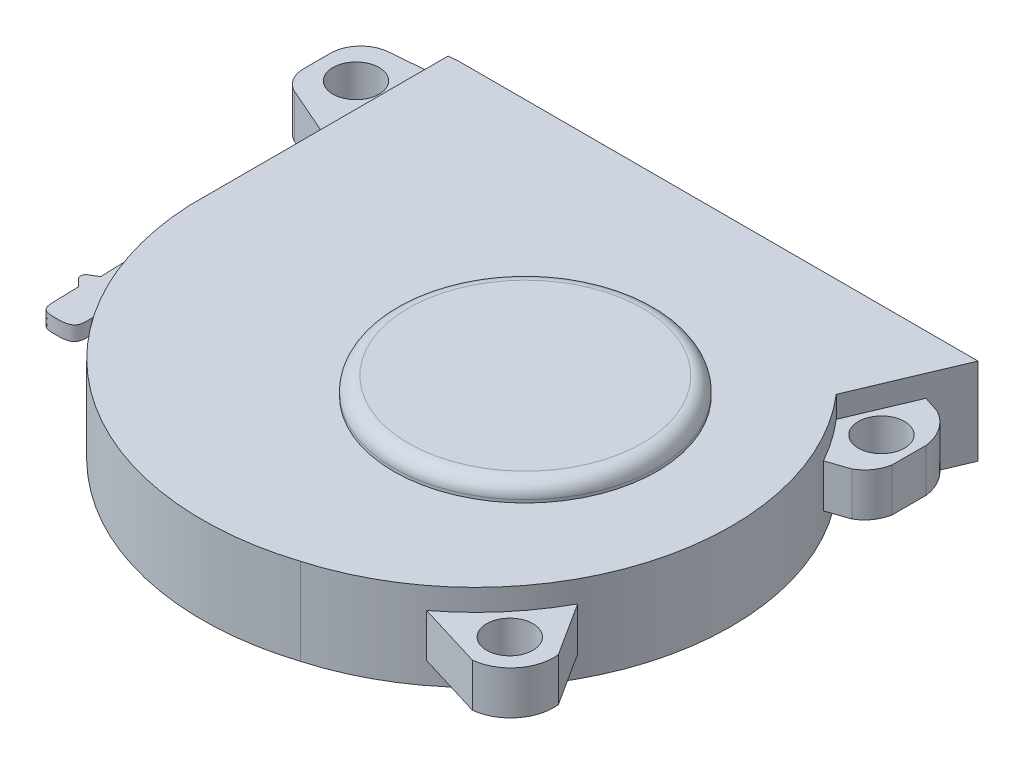
SolidWorks part; units mm, degrees
ref_plane "Front" through (0, 0, 0) normal (0, 0, 1) x (1, 0, 0)
ref_plane "Top" through (0, 0, 0) normal (0, 1, 0) x (1, 0, 0)
ref_plane "Right" through (0, 0, 0) normal (1, 0, 0) x (0, 0, -1)
sketch "Sketch1" plane through (0, 0, 0) normal (0, 1, 0) x (1, 0, 0)
  line L0 (-18.6292, 17.0403) -> (20.0618, 17.0403)
  line L1 (17.6528, 17.8425) -> (14.4091, 10.1398)
  line L2 (16.249, 14.5088) -> (17.4134, 14.1194)
  line L3 (16.45, 7.2111) -> (17.9281, 7.7132)
  line L4 (19.0692, 11.7013) -> (19.0692, 8.3745)
  line L5 (16.5199, -9.8679) -> (19.6981, -14.8328)
  line L6 (11.6896, -15.4846) -> (18.2309, -17.4822)
  line L7 (-18.6292, 17.0403) -> (-27.3062, 16.322)
  line L8 (-25.0308, 14.4047) -> (-25.0308, 12.7056)
  line L9 (-19.2931, 9.001) -> (-28.2152, 12.8944)
  line L10 (-19.2931, -0.9359) -> (-19.2931, 20.8935)
  line L11 (-22.0907, 5.8392) -> (-19.2931, 5.8392)
  line L12 (-23.3574, 4.7836) -> (-23.0966, -3.2535)
  line L13 (-23.0966, -3.2535) -> (-23.6215, -3.5769)
  line L14 (-23.672, -4.2219) -> (-23.0966, -4.7998)
  line L15 (-23.1924, -6.9309) -> (-23.3094, -2.3969)
  line L16 (-20.9157, -6.081) -> (-21.4467, 6.5849)
  line L17 (-20.5996, -3.5931) -> (-21.2439, -3.2731)
  line L18 (-20.5996, -4.1555) -> (-21.1733, -4.78)
  circle A0 centre (-22.4948, 13.8104) radius 1.5
  arc A1 (5.8687, -18.4026) -> (14.4091, 10.1398) centre (0.983, -1.3918) ccw
  arc A2 (5.8687, -18.4026) -> (-19.2931, -0.9359) centre (0, 0) cw
  arc A3 (17.4134, 14.1194) -> (19.0692, 11.7013) centre (15.8644, 11.2827) cw
  arc A4 (17.9281, 7.7132) -> (19.0665, 9.3395) centre (16.7476, 9.7511) ccw
  circle A5 centre (16.8946, 10.7771) radius 1.5
  arc A6 (16.249, -16.8769) -> (18.8914, -13.5727) centre (15.9284, -13.9118) ccw
  circle A7 centre (16.154, -14.1957) radius 1.5
  arc A8 (-25.0308, 14.4047) -> (-23.1116, 16.6692) centre (-22.921, 14.5621) cw
  arc A9 (-25.0308, 12.7056) -> (-23.8371, 10.9839) centre (-23.1924, 12.7056) ccw
  arc A10 (-22.0907, 5.8392) -> (-23.3574, 4.7836) centre (-22.172, 4.649) ccw
  arc A11 (-20.5996, -3.5931) -> (-20.5996, -4.1555) centre (-20.8323, -3.8743) cw
  spline S0 degree 3 poles (-23.2029, -6.5236) (-23.1904, -6.7014) (-23.1459, -7.158) (-22.6046, -7.2916) (-22.1311, -7.3011) (-21.6116, -7.3012) (-20.8501, -7.06) (-20.9152, -6.3528) (-20.9157, -6.081) knots 0 0 0 0 0.172348 0.293809 0.415161 0.571057 0.73062 1 1 1 1
  spline S1 degree 3 poles (-21.2488, 1.8965) (-21.2551, 2.2821) (-21.2272, 3.1094) (-20.2629, 3.6348) (-19.6377, 3.6409) (-19.2931, 3.5168) knots 0 0 0 0 0.425412 0.645509 1 1 1 1
sketch "Sketch2" plane through (0, 0, 0) normal (0, 1, 0) x (1, 0, 0)
  line L0 (16.45, 7.2111) -> (17.9281, 7.7132) construction
  line L1 (16.249, 14.5088) -> (17.4134, 14.1194) construction
  line L2 (-21.0289, -3.3799) -> (-21.2542, 1.9932)
  line L3 (17.6528, 17.8425) -> (14.4091, 10.1398) construction
  line L4 (-19.2931, -0.9359) -> (-19.2931, 20.8935) construction
  line L6 (-18.6292, 17.0403) -> (-27.3062, 16.322) construction
  line L7 (-25.0308, 14.4047) -> (-25.0308, 12.7056) construction
  line L8 (11.6896, -15.4846) -> (18.2309, -17.4822) construction
  line L9 (16.5199, -9.8679) -> (19.6981, -14.8328) construction
  line L10 (-23.672, -4.2219) -> (-23.0966, -4.7998) construction
  line L11 (-22.0907, 5.8392) -> (-19.2931, 5.8392) construction
  line L12 (-23.3574, 4.7836) -> (-23.0966, -3.2535) construction
  line L13 (-23.0966, -3.2535) -> (-23.6215, -3.5769) construction
  line L14 (-19.2931, 9.001) -> (-28.2152, 12.8944) construction
  line L15 (-20.9157, -6.081) -> (-21.4467, 6.5849) construction
  line L16 (-20.5996, -3.5931) -> (-21.2439, -3.2731) construction
  line L17 (-20.5996, -4.1555) -> (-21.1733, -4.78) construction
  line L18 (-23.1924, -6.9309) -> (-23.3094, -2.3969) construction
  line L19 (16.45, 7.2111) -> (17.9281, 7.7132)
  line L20 (16.249, 14.5088) -> (17.4134, 14.1194)
  line L21 (19.0692, 11.7013) -> (19.0665, 9.3395)
  line L22 (17.315, 17.0403) -> (16.249, 14.5088)
  line L23 (-19.2931, -0.9359) -> (-19.2931, 3.5547)
  line L24 (-18.6292, 17.0403) -> (17.315, 17.0403)
  line L25 (-18.6292, 17.0403) -> (-23.1116, 16.6692)
  line L26 (-25.0308, 14.4047) -> (-25.0308, 12.7056)
  line L27 (11.6896, -15.4846) -> (16.249, -16.8769)
  line L28 (16.5199, -9.8679) -> (18.8914, -13.5727)
  line L29 (-23.672, -4.2219) -> (-23.2514, -4.6443)
  line L30 (-22.0907, 5.8392) -> (-19.2931, 5.8392)
  line L31 (-23.3574, 4.7836) -> (-23.0966, -3.2535)
  line L32 (-23.0966, -3.2535) -> (-23.6215, -3.5769)
  line L33 (-19.2931, 9.001) -> (-24.0162, 11.0621)
  line L34 (-20.9157, -6.081) -> (-20.9791, -4.5686)
  line L35 (-20.5996, -3.5931) -> (-21.0289, -3.3799)
  line L36 (-20.5996, -4.1555) -> (-20.9791, -4.5686)
  line L37 (-23.1924, -6.9309) -> (-23.2514, -4.6443)
  line L38 (-19.2931, 5.8392) -> (-19.2931, 9.001)
  arc A0 (17.9281, 7.7132) -> (19.0665, 9.3395) centre (16.7476, 9.7511) ccw construction
  circle A1 centre (-22.4948, 13.8104) radius 1.5
  circle A2 centre (-22.4948, 13.8104) radius 1.5
  circle A3 centre (16.154, -14.1957) radius 1.5
  circle A4 centre (16.154, -14.1957) radius 1.5
  circle A5 centre (16.8946, 10.7771) radius 1.5
  circle A6 centre (16.8946, 10.7771) radius 1.5
  arc A7 (19.0692, 11.7013) -> (17.4134, 14.1194) centre (15.8644, 11.2827) ccw construction
  arc A8 (5.8687, -18.4026) -> (14.4091, 10.1398) centre (0.983, -1.3918) ccw construction
  arc A9 (-19.2931, -0.9359) -> (5.8687, -18.4026) centre (0, 0) ccw construction
  arc A10 (-25.0308, 12.7056) -> (-23.8371, 10.9839) centre (-23.1924, 12.7056) ccw construction
  arc A11 (-23.1116, 16.6692) -> (-25.0308, 14.4047) centre (-22.921, 14.5621) ccw construction
  arc A12 (16.249, -16.8769) -> (18.8914, -13.5727) centre (15.9284, -13.9118) ccw construction
  arc A13 (-22.0907, 5.8392) -> (-23.3574, 4.7836) centre (-22.172, 4.649) ccw construction
  arc A14 (-20.5996, -4.1555) -> (-20.5996, -3.5931) centre (-20.8323, -3.8743) ccw construction
  arc A15 (17.9281, 7.7132) -> (19.0665, 9.3395) centre (16.7476, 9.7511) ccw
  arc A16 (19.0692, 11.7013) -> (17.4134, 14.1194) centre (15.8644, 11.2827) ccw
  arc A17 (5.8687, -18.4026) -> (11.6896, -15.4846) centre (0.983, -1.3918) ccw
  arc A18 (-19.2931, -0.9359) -> (5.8687, -18.4026) centre (0, 0) ccw
  arc A19 (-25.0308, 12.7056) -> (-24.0162, 11.0621) centre (-23.1924, 12.7056) ccw
  arc A20 (-23.1116, 16.6692) -> (-25.0308, 14.4047) centre (-22.921, 14.5621) ccw
  arc A21 (16.249, -16.8769) -> (18.8914, -13.5727) centre (15.9284, -13.9118) ccw
  arc A22 (-22.0907, 5.8392) -> (-23.3574, 4.7836) centre (-22.172, 4.649) ccw
  arc A23 (-20.5996, -4.1555) -> (-20.5996, -3.5931) centre (-20.8323, -3.8743) ccw
  arc A24 (16.5199, -9.8679) -> (16.45, 7.2111) centre (0.983, -1.3918) ccw
  arc A25 (-23.6215, -3.5769) -> (-23.672, -4.2219) centre (-23.4577, -3.9141) ccw
  spline S0 degree 3 poles (-836.0405, -1833.7431) (22.564, 54.1067) (-27.65, -6.0462) (-22.6046, -7.2916) (-22.1311, -7.3011) (-21.6116, -7.3012) (-15.3022, -5.3029) (-83.7411, 60.0295) (1142.5595, -1632.69) knots -3.454911 -3.454911 -3.454911 -3.454911 0.172348 0.293809 0.415161 0.571057 0.73062 5.260852 5.260852 5.260852 5.260852 only from (-23.2029, -6.5236) to (-20.9157, -6.081) construction
  spline S2 degree 3 poles (-23.2029, -6.5236) (-23.1904, -6.7014) (-23.1459, -7.158) (-22.6046, -7.2916) (-22.1311, -7.3011) (-21.6116, -7.3012) (-20.8501, -7.06) (-20.9152, -6.3528) (-20.9157, -6.081) knots 0 0 0 0 0.172348 0.293809 0.415161 0.571057 0.73062 1 1 1 1
  spline S3 degree 3 poles (-21.2542, 1.9932) (-21.2501, 2.3772) (-21.1951, 3.186) (-20.238, 3.678) (-19.6263, 3.675) (-19.2931, 3.5547) knots 0.008573 0.008573 0.008573 0.008573 0.425412 0.645509 0.988656 0.988656 0.988656 0.988656
  dimension "D1" = 0
  dimension "D2" = 0
  dimension "D3" = 0
extrude "Boss-Extrude1" add sketch "Sketch2" along normal mid plane 6 contours L2 S3 L23 A18 A17 L27 A21 L28 A24 L19 A15 L21 A16 L20 L22 L24 L25 A20 L26 A19 L33 L38 L30 A22 L31 L32 A25 L29 L37 S2 L34 L36 A23 L35 A2 A4 A6
sketch "Sketch3" plane through (0, 3, 0) normal (0, 1, 0) x (1, 0, 0)
  circle A12 centre (3.7314, -0.699) radius 9.096
extrude "Boss-Extrude2" add sketch "Sketch3" along normal blind 1.2
fillet "Fillet1" radius 1 1 edges at (3.7314, 4.2, 9.795)
sketch "Sketch4" plane through (0, 3, 0) normal (0, 1, 0) x (1, 0, 0)
  line L0 (-19.2931, 7.2487) -> (-19.2931, 22.0832)
  line L1 (-19.2931, -0.9359) -> (-19.2931, 20.8935) construction
  line L2 (-19.2931, 22.0832) -> (-29.9041, 22.0832)
  line L3 (-29.9041, 22.0832) -> (-28.7932, 8.6635)
  line L4 (-28.7932, 8.6635) -> (-19.2931, 7.2487)
  line L5 (17.6528, 17.8425) -> (14.4091, 10.1398)
  line L6 (17.6528, 17.8425) -> (30.1756, 15.0434)
  line L7 (30.1756, 15.0434) -> (25.3477, 2.0452)
  line L8 (25.3477, 2.0452) -> (18.187, 2.7627)
  line L9 (17.2798, -8.2948) -> (24.5758, -15.2761)
  line L10 (24.5758, -15.2761) -> (17.2798, -23.8722)
  line L11 (17.2798, -23.8722) -> (10.6704, -16.2037)
  arc A0 (5.8687, -18.4026) -> (14.4091, 10.1398) centre (0.983, -1.3918) ccw construction
  arc A2 (10.6704, -16.2037) -> (17.2798, -8.2948) centre (0.983, -1.3918) ccw
  arc A3 (18.187, 2.7627) -> (14.4091, 10.1398) centre (0.983, -1.3918) ccw
extrude "Cut-Extrude1" cut sketch "Sketch4" against normal blind 1.5
sketch "Sketch5" plane through (0, -3, 0) normal (0, -1, 0) x (1, 0, 0)
  line L3 (24.5758, 15.2761) -> (17.2798, 23.8722)
  line L4 (14.4091, -10.1398) -> (17.6528, -17.8425)
  line L5 (25.3477, -2.0452) -> (18.187, -2.7627)
  line L6 (30.1756, -15.0434) -> (25.3477, -2.0452)
  line L7 (17.6528, -17.8425) -> (30.1756, -15.0434)
  line L8 (14.4091, -10.1398) -> (17.6528, -17.8425)
  line L9 (25.3477, -2.0452) -> (18.187, -2.7627)
  line L10 (30.1756, -15.0434) -> (25.3477, -2.0452)
  line L11 (17.6528, -17.8425) -> (30.1756, -15.0434)
  line L12 (-19.2931, -22.0832) -> (-19.2931, -7.2487)
  line L13 (-29.9041, -22.0832) -> (-19.2931, -22.0832)
  line L14 (-28.7932, -8.6635) -> (-29.9041, -22.0832)
  line L15 (-19.2931, -7.2487) -> (-28.7932, -8.6635)
  line L16 (-19.2931, -22.0832) -> (-19.2931, -7.2487)
  line L17 (-29.9041, -22.0832) -> (-19.2931, -22.0832)
  line L18 (-28.7932, -8.6635) -> (-29.9041, -22.0832)
  line L19 (-19.2931, -7.2487) -> (-28.7932, -8.6635)
  line L20 (17.2798, 23.8722) -> (10.6704, 16.2037)
  line L21 (17.2798, 8.2948) -> (24.5758, 15.2761)
  line L22 (24.5758, 15.2761) -> (17.2798, 23.8722)
  line L23 (17.2798, 23.8722) -> (10.6704, 16.2037)
  line L24 (17.2798, 8.2948) -> (24.5758, 15.2761)
  arc A1 (14.4091, -10.1398) -> (18.187, -2.7627) centre (0.983, 1.3918) ccw
  arc A2 (14.4091, -10.1398) -> (18.187, -2.7627) centre (0.983, 1.3918) ccw
  arc A3 (17.2798, 8.2948) -> (10.6704, 16.2037) centre (0.983, 1.3918) ccw
  arc A4 (17.2798, 8.2948) -> (10.6704, 16.2037) centre (0.983, 1.3918) ccw
  dimension "D1" = 0
  dimension "D2" = 0
  dimension "D3" = 0
extrude "Cut-Extrude2" cut sketch "Sketch5" against normal blind 1.5
sketch "Sketch6" plane through (0, 3, 0) normal (0, 1, 0) x (1, 0, 0)
  line L0 (-19.2931, -0.9359) -> (-19.2931, 20.8935) construction
  line L1 (-19.2931, -0.9359) -> (-19.2931, 7.436)
  line L2 (-19.2931, 7.436) -> (-28.4198, 7.1113)
  line L3 (-28.4198, 7.1113) -> (-26.7421, -11.6689)
  line L4 (-26.7421, -11.6689) -> (-19.2931, -11.0034)
  line L5 (-19.2931, -11.0034) -> (-19.2931, -0.9359)
extrude "Cut-Extrude3" cut sketch "Sketch6" against normal blind 5
sketch "Sketch7" plane through (0, 3, 0) normal (0, 1, 0) x (1, 0, 0)
  line L0 (-22.4948, 13.8104) -> (-19.2931, 13.8104)
  line L1 (-19.2931, -0.9359) -> (-19.2931, 16.9853) construction
  line L2 (-22.4948, 13.8104) -> (-22.4948, 17.0403)
  line L3 (-22.4948, 13.8104) -> (16.8946, 13.8104)
  line L4 (16.8946, 10.7771) -> (16.8946, 13.8104)
  line L5 (16.8946, 10.7771) -> (16.8946, -14.1957)
  line L6 (16.8946, -14.1957) -> (16.154, -14.1957)
  dimension "D1" = 3.2018
  dimension "D2" = 3.2299
  dimension "D3" = 39.3894
  dimension "D4" = 3.0333
  dimension "D5" = 24.9729
other "Move Face1" face at (16.154, 1.5, 15.6957) face at (-22.4948, -1.5, -12.3104) face at (16.8946, 1.5, -9.2771) parameters "D1"=0.1
